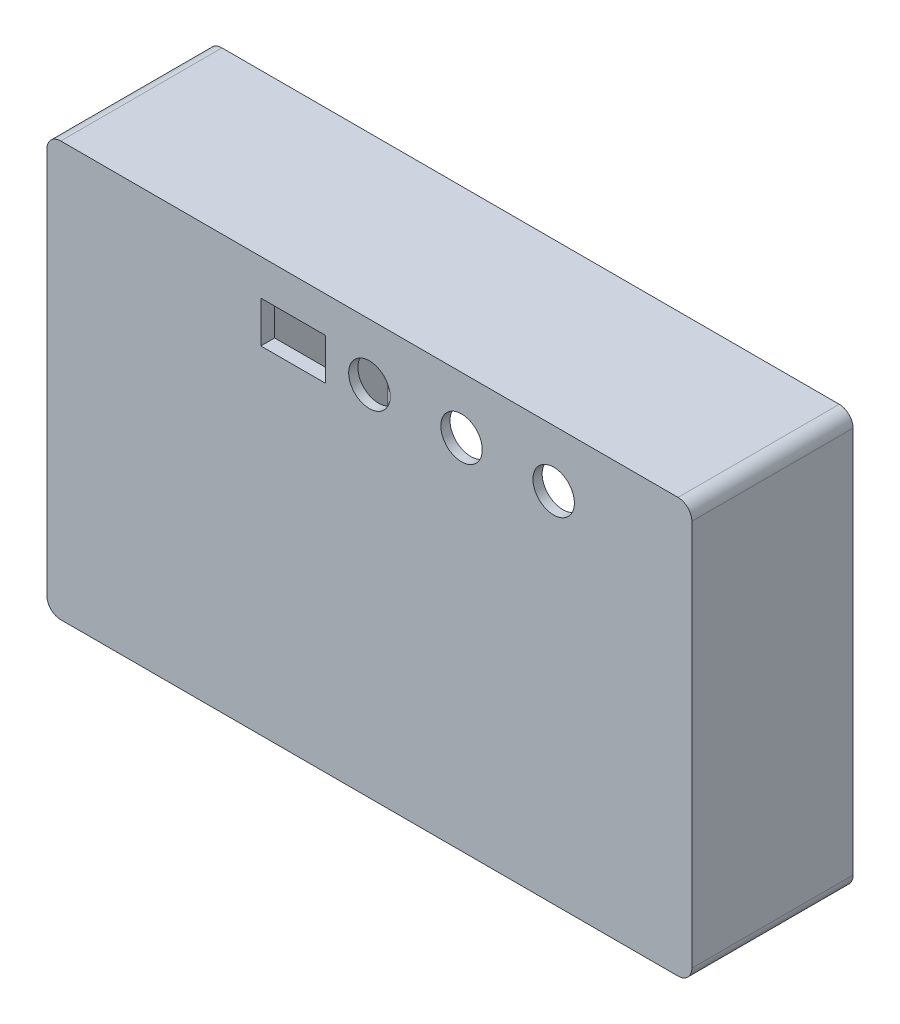
SolidWorks part; units mm, degrees
ref_plane "前视基准面" through (0, 0, 0) normal (0, 0, 1) x (1, 0, 0)
ref_plane "上视基准面" through (0, 0, 0) normal (0, 1, 0) x (1, 0, 0)
ref_plane "右视基准面" through (0, 0, 0) normal (1, 0, 0) x (0, 0, -1)
other "Configuration Table"
sketch "草图4" plane through (0, 0, 0) normal (0, 0, 1) x (1, 0, 0)
  line L5 (67, 0) -> (-67, 0)
  line L6 (70, 3) -> (70, 87)
  line L7 (67, 90) -> (-67, 90)
  line L8 (-70, 3) -> (-70, 87)
  arc A4 (-67, 90) -> (-70, 87) centre (-67, 87) ccw
  arc A5 (-67, 0) -> (-70, 3) centre (-67, 3) cw
  arc A6 (67, 0) -> (70, 3) centre (67, 3) ccw
  arc A7 (70, 87) -> (67, 90) centre (67, 87) ccw
  point P5 (0, 0)
  dimension "D1" = 3
extrude "凸台-拉伸2" add sketch "草图4" against normal blind 35
sketch "草图5" plane through (0, 0, -35) normal (0, 0, -1) x (-1, 0, 0)
  line L0 (0, 0) -> (0, 90) construction
  line L1 (-67, 90) -> (67, 90) construction
  line L2 (-70, 45) -> (70, 45) construction
  line L3 (-70, 3) -> (-70, 87) construction
  line L4 (70, 87) -> (70, 3) construction
  line L10 (-64.5, 87.5) -> (64.5, 87.5)
  line L11 (-67.5, 84.5) -> (-67.5, 5.5)
  line L12 (-64.5, 2.5) -> (64.5, 2.5)
  line L13 (67.5, 84.5) -> (67.5, 5.5)
  arc A4 (-67.5, 5.5) -> (-64.5, 2.5) centre (-64.5, 5.5) ccw
  arc A5 (64.5, 2.5) -> (67.5, 5.5) centre (64.5, 5.5) ccw
  arc A6 (64.5, 87.5) -> (67.5, 84.5) centre (64.5, 84.5) cw
  arc A7 (-64.5, 87.5) -> (-67.5, 84.5) centre (-64.5, 84.5) ccw
  point P15 (0, 87.5)
  point P16 (-67.5, 45)
  dimension "D1" = 3
extrude "切除-拉伸3" cut sketch "草图5" against normal blind 5
sketch "草图7" plane through (0, 0, -30) normal (0, 0, -1) x (-1, 0, 0)
  line L0 (0, 0) -> (0, 90) construction
  line L1 (-67, 90) -> (67, 90) construction
  line L2 (-67.5, 45) -> (67.5, 45) construction
  line L3 (-67.5, 84.5) -> (-67.5, 5.5) construction
  line L4 (67.5, 5.5) -> (67.5, 84.5) construction
  line L5 (62, 5) -> (65, 5)
  line L6 (-62, 85) -> (62, 85)
  line L7 (-65, 82) -> (-65, 8)
  line L8 (-62, 5) -> (62, 5)
  line L9 (65, 82) -> (65, 8)
  line L10 (65, 5) -> (65, 8)
  arc A0 (-65, 8) -> (-62, 5) centre (-62, 8) ccw
  arc A2 (62, 85) -> (65, 82) centre (62, 82) cw
  arc A3 (-62, 85) -> (-65, 82) centre (-62, 82) ccw
  point P15 (65, 45)
  point P16 (0, 5)
  dimension "D1" = 3
extrude "切除-拉伸4" cut sketch "草图7" against normal blind 27
sketch "草图8" plane through (0, 0, -3) normal (0, 0, -1) x (-1, 0, 0)
  line L0 (-65, 45) -> (65, 45) construction
  line L5 (-65, 82) -> (-65, 8) construction
  line L6 (65, 5) -> (65, 82) construction
  line L7 (-58.3546, 12.85) -> (-56.7091, 10)
  line L8 (-56.7091, 80) -> (-58.3546, 82.85)
  line L9 (-58.3546, 82.85) -> (-61.6454, 82.85)
  line L10 (-61.6454, 82.85) -> (-63.2909, 80)
  line L11 (-63.2909, 80) -> (-61.6454, 77.15)
  line L12 (-61.6454, 77.15) -> (-58.3546, 77.15)
  line L13 (-58.3546, 77.15) -> (-56.7091, 80)
  line L14 (-61.6454, 12.85) -> (-58.3546, 12.85)
  line L15 (-63.2909, 10) -> (-61.6454, 12.85)
  line L16 (-61.6454, 7.15) -> (-63.2909, 10)
  line L17 (-58.3546, 7.15) -> (-61.6454, 7.15)
  line L18 (-56.7091, 10) -> (-58.3546, 7.15)
  line L19 (-17.8427, 20.9245) -> (-17.8427, 70.9245) construction
  line L30 (-52.8427, 70.9245) -> (17.1573, 70.9245) construction
  line L31 (-52.8427, 70.9245) -> (-52.8427, 20.9245) construction
  line L32 (-52.8427, 20.9245) -> (17.1573, 20.9245) construction
  line L33 (17.1573, 70.9245) -> (17.1573, 20.9245) construction
  line L40 (17.76, 68.9245) -> (16.4587, 71.1785)
  line L41 (16.4587, 71.1785) -> (13.856, 71.1785)
  line L42 (13.856, 71.1785) -> (12.5547, 68.9245)
  line L43 (12.5547, 68.9245) -> (13.856, 66.6705)
  line L44 (13.856, 66.6705) -> (16.4587, 66.6705)
  line L45 (16.4587, 66.6705) -> (17.76, 68.9245)
  line L46 (-52.144, 66.6705) -> (-53.4453, 68.9245)
  line L47 (-49.5413, 66.6705) -> (-52.144, 66.6705)
  line L48 (-48.24, 68.9245) -> (-49.5413, 66.6705)
  line L49 (-49.5413, 71.1785) -> (-48.24, 68.9245)
  line L50 (-52.144, 71.1785) -> (-49.5413, 71.1785)
  line L51 (-53.4453, 68.9245) -> (-52.144, 71.1785)
  line L64 (0, 0) -> (0, 87.5) construction
  line L65 (64.5, 87.5) -> (-64.5, 87.5) construction
  line L72 (58.3546, 77.15) -> (56.7091, 80)
  line L73 (61.6454, 77.15) -> (58.3546, 77.15)
  line L74 (63.2909, 80) -> (61.6454, 77.15)
  line L75 (61.6454, 82.85) -> (63.2909, 80)
  line L76 (58.3546, 82.85) -> (61.6454, 82.85)
  line L77 (56.7091, 80) -> (58.3546, 82.85)
  line L78 (15.1573, 22) -> (15.1573, 5.9013) construction
  line L79 (-60, 10) -> (15.1573, 10) construction
  line L86 (8.3546, 7.15) -> (6.7091, 10)
  line L87 (11.6454, 7.15) -> (8.3546, 7.15)
  line L88 (13.2909, 10) -> (11.6454, 7.15)
  line L89 (11.6454, 12.85) -> (13.2909, 10)
  line L90 (8.3546, 12.85) -> (11.6454, 12.85)
  line L91 (6.7091, 10) -> (8.3546, 12.85)
  line L92 (-52.8427, 45.9245) -> (17.1573, 45.9245) construction
  line L93 (-49.5413, 25.1785) -> (-52.144, 25.1785)
  line L94 (-48.24, 22.9245) -> (-49.5413, 25.1785)
  line L95 (-49.5413, 20.6705) -> (-48.24, 22.9245)
  line L96 (-52.144, 20.6705) -> (-49.5413, 20.6705)
  line L97 (-53.4453, 22.9245) -> (-52.144, 20.6705)
  line L98 (-52.144, 25.1785) -> (-53.4453, 22.9245)
  line L99 (16.4587, 25.1785) -> (17.76, 22.9245)
  line L100 (13.856, 25.1785) -> (16.4587, 25.1785)
  line L101 (12.5547, 22.9245) -> (13.856, 25.1785)
  line L102 (13.856, 20.6705) -> (12.5547, 22.9245)
  line L103 (16.4587, 20.6705) -> (13.856, 20.6705)
  line L104 (17.76, 22.9245) -> (16.4587, 20.6705)
  line L105 (6.7091, 10) -> (13.2909, 10) construction
  line L107 (62, 85) -> (-62, 85) construction
  line L109 (-67.5, 84.5) -> (-67.5, 5.5) construction
  circle A0 centre (-60, 80) radius 2.85 construction
  circle A1 centre (-60, 10) radius 2.85 construction
  circle A2 centre (15.1573, 68.9245) radius 2.254 construction
  circle A3 centre (10, 10) radius 2.85 construction
  circle A4 centre (60, 80) radius 2.85 construction
  dimension "D1" = 2
  dimension "D3" = 70
  dimension "D4" = 5.7
  dimension "D2" = 2
  dimension "D5" = 5
  dimension "D6" = 5
  dimension "D7" = 5
  dimension "D8" = 7.5
extrude "切除-拉伸5" cut sketch "草图8" against normal blind 2
sketch "草图9" plane through (0, 0, -3) normal (0, 0, -1) x (-1, 0, 0)
  line L0 (-53.8891, 77.6852) -> (21.4482, 77.6852) construction
  line L1 (-13.0718, 77.6852) -> (-16.5359, 83.6852)
  line L2 (-33.0718, 77.6852) -> (-36.5359, 83.6852)
  line L3 (-36.5359, 83.6852) -> (-43.4641, 83.6852)
  line L4 (-43.4641, 83.6852) -> (-46.9282, 77.6852)
  line L5 (-46.9282, 77.6852) -> (-43.4641, 71.6852)
  line L6 (-43.4641, 71.6852) -> (-36.5359, 71.6852)
  line L7 (-36.5359, 71.6852) -> (-33.0718, 77.6852)
  line L8 (-16.5359, 83.6852) -> (-23.4641, 83.6852)
  line L9 (-23.4641, 83.6852) -> (-26.9282, 77.6852)
  line L10 (-26.9282, 77.6852) -> (-23.4641, 71.6852)
  line L11 (-23.4641, 71.6852) -> (-16.5359, 71.6852)
  line L12 (-16.5359, 71.6852) -> (-13.0718, 77.6852)
  line L13 (6.9282, 77.6852) -> (3.4641, 83.6852)
  line L14 (3.4641, 83.6852) -> (-3.4641, 83.6852)
  line L15 (-3.4641, 83.6852) -> (-6.9282, 77.6852)
  line L16 (-6.9282, 77.6852) -> (-3.4641, 71.6852)
  line L17 (-3.4641, 71.6852) -> (3.4641, 71.6852)
  line L18 (3.4641, 71.6852) -> (6.9282, 77.6852)
  circle A1 centre (-40, 77.6852) radius 6 construction
  dimension "D1" = 3
extrude "切除-拉伸6" cut sketch "草图9" against normal blind 1
sketch "草图10" plane through (0, 0, -2) normal (0, 0, -1) x (-1, 0, 0)
  line L0 (-46.9282, 77.6852) -> (-33.0718, 77.6852) construction
  line L1 (-33.0718, 77.6852) -> (-36.5359, 83.6852) construction
  line L2 (-43.4641, 83.6852) -> (-36.5359, 71.6852) construction
  circle A0 centre (-40, 77.6852) radius 4.5
  circle A1 centre (-20, 77.6852) radius 4.5
  circle A2 centre (0, 77.6852) radius 4.5
  dimension "D1" = 3
extrude "切除-拉伸7" cut sketch "草图10" against normal blind 2
sketch "草图11" plane through (0, 0, -3) normal (0, 0, -1) x (-1, 0, 0)
  line L5 (65, 5) -> (65, 73) construction
  line L6 (65, 5) -> (65, 82) construction
  line L7 (65, 73) -> (30, 73) construction
  line L8 (30, 73) -> (30, 5) construction
  line L9 (-62, 5) -> (65, 5) construction
  line L10 (30, 5) -> (65, 5) construction
  line L11 (30, 73) -> (65, 73)
  line L12 (30, 73) -> (30, 58)
  line L13 (30, 58) -> (65, 58)
  line L14 (65, 73) -> (65, 58)
  line L15 (30, 5) -> (58, 5)
  line L16 (30, 5) -> (30, 17)
  line L17 (30, 17) -> (58, 17)
  line L18 (58, 5) -> (58, 17)
  line L19 (30, 47.5373) -> (65, 47.5373)
  line L20 (30, 47.5373) -> (30, 32.5373)
  line L21 (30, 32.5373) -> (65, 32.5373)
  line L22 (65, 47.5373) -> (65, 32.5373)
extrude "凸台-拉伸3" add sketch "草图11" along normal blind 5
sketch "草图12" plane through (0, 0, -3) normal (0, 0, -1) x (-1, 0, 0)
  line L0 (-62, 5) -> (65, 5) construction
  line L2 (30, 73) -> (30, 5)
  line L3 (30, 5) -> (25, 5)
  line L4 (25, 73) -> (25, 5)
  line L6 (30, 73) -> (43, 73)
  line L7 (25, 73) -> (25, 78)
  line L8 (25, 78) -> (43, 78)
  line L9 (43, 73) -> (43, 78)
extrude "凸台-拉伸5" add sketch "草图12" along normal blind 26
sketch "草图13" plane through (0, 0, -3) normal (0, 0, -1) x (-1, 0, 0)
  line L0 (6.9282, 77.6852) -> (52.6338, 77.6852) construction
  line L1 (9.5662, 82.1852) -> (23.5662, 82.1852)
  line L2 (9.5662, 82.1852) -> (9.5662, 73.1852)
  line L3 (9.5662, 73.1852) -> (23.5662, 73.1852)
  line L4 (23.5662, 82.1852) -> (23.5662, 73.1852)
  point P7 (9.5662, 77.6852)
extrude "切除-拉伸8" cut sketch "草图13" against normal blind 3
